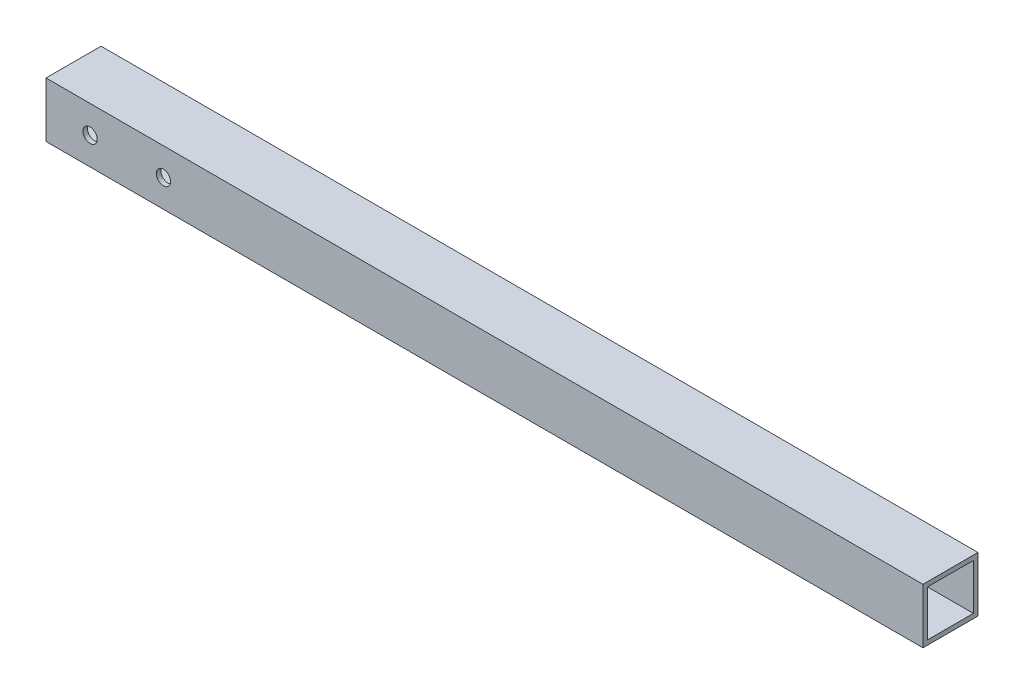
SolidWorks part; units mm, degrees
material "Stainless Steel (ferritic)"
ref_plane "Front Plane" through (0, 0, 0) normal (0, 0, 1) x (1, 0, 0)
ref_plane "Top Plane" through (0, 0, 0) normal (0, 1, 0) x (1, 0, 0)
ref_plane "Right Plane" through (0, 0, 0) normal (1, 0, 0) x (0, 0, -1)
sketch "Sketch1" plane through (0, 0, 0) normal (1, 0, 0) x (0, 0, -1)
  line L0 (-6.25, 6.25) -> (-6.25, -6.25)
  line L1 (-7.5, 7.5) -> (7.5, 7.5)
  line L2 (-7.5, 7.5) -> (-7.5, -7.5)
  line L3 (-7.5, -7.5) -> (7.5, -7.5)
  line L4 (7.5, 7.5) -> (7.5, -7.5)
  line L5 (-7.5, 7.5) -> (7.5, -7.5) construction
  line L6 (-7.5, -7.5) -> (7.5, 7.5) construction
  line L7 (-6.25, -6.25) -> (6.25, -6.25)
  line L8 (6.25, 6.25) -> (6.25, -6.25)
  line L9 (-6.25, 6.25) -> (6.25, 6.25)
  point P0 (0, 0)
  dimension "D1" = 15
  dimension "D2" = 1.25
extrude "Boss-Extrude1" add sketch "Sketch1" along normal blind 238.95
sketch "Sketch2" plane through (0, 0, -7.5) normal (0, 0, -1) x (-1, 0, 0)
  line L0 (0, 0) -> (-238.95, 0) construction
  line L1 (0, -7.5) -> (0, 7.5) construction
  line L2 (-238.95, -7.5) -> (-238.95, 7.5) construction
  line L3 (-22, 7.5) -> (-22, -7.5) construction
  line L4 (-238.95, 7.5) -> (0, 7.5) construction
  line L5 (-238.95, -7.5) -> (0, -7.5) construction
  circle A0 centre (-12, 0) radius 1.95
  circle A1 centre (-32, 0) radius 1.95
  dimension "D3" = 3.9
  dimension "D1" = 20
  dimension "D2" = 32
extrude "Cut-Extrude1" cut sketch "Sketch2" against normal through all
sketch "Sketch3" [suppressed] plane through (0, 0, -7.5) normal (0, 0, 1) x (1, 0, 0)
  line L0 (0, 0) -> (189.575, 0) construction
  line L1 (0, 7.5) -> (0, -7.5) construction
  line L2 (189.575, 7.5) -> (189.575, -7.5) construction
  line L3 (0, -7.5) -> (0, 7.5) construction
  circle A0 centre (71.275, 0) radius 3.75
  circle A1 centre (71.275, 0) radius 3.75 construction
  dimension "D2" = 7.5
  dimension "D1" = 71.275
sketch "Sketch4" plane through (0, -7.5, 0) normal (0, -1, 0) x (1, 0, 0)
  circle A0 centre (172.8936, -0.8188) radius 2.5
  dimension "D1" = 5
sketch "Sketch5" plane through (0, -7.5, 0) normal (0, -1, 0) x (1, 0, 0)
  line L0 (0, 7.5) -> (0, -7.5) construction
  line L1 (-1000, 0) -> (49000, 0) construction
  line L2 (238.95, 7.5) -> (238.95, -7.5) construction
  circle A0 centre (64.7, 0) radius 3.75
  circle A1 centre (228.95, 0) radius 2
  point P7 (0, 0)
  dimension "D2" = 7.5
  dimension "D3" = 4
  dimension "D1" = 64.7
  dimension "D4" = 10
extrude "Cut-Extrude6" cut sketch "Sketch5" against normal blind 5
